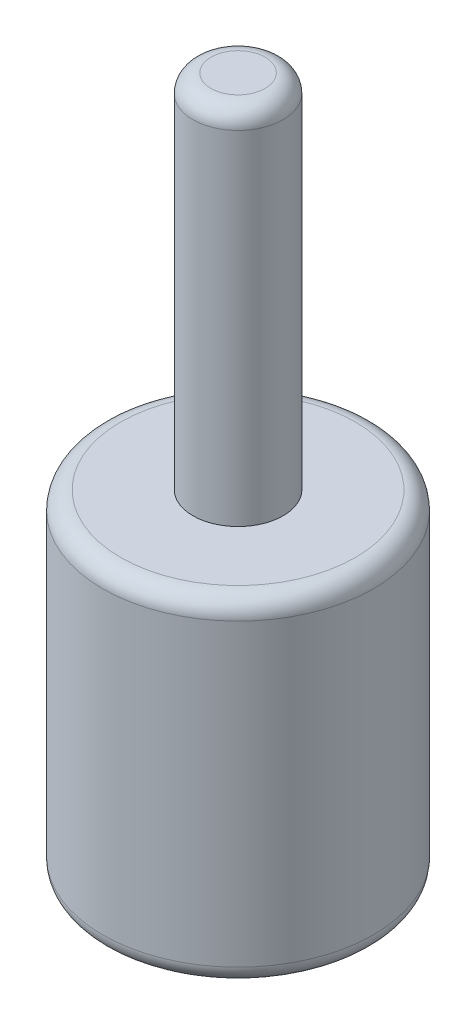
SolidWorks part; units mm, degrees
ref_plane "Plano frontal" through (0, 0, 0) normal (0, 0, 1) x (1, 0, 0)
ref_plane "Plano superior" through (0, 0, 0) normal (0, 1, 0) x (1, 0, 0)
ref_plane "Plano direito" through (0, 0, 0) normal (1, 0, 0) x (0, 0, -1)
sketch "Esboço1" plane through (0, 0, 0) normal (0, 1, 0) x (1, 0, 0)
  circle A0 centre (-2.1312, 0) radius 7.5
  dimension "D1" = 15
extrude "Ressalto-extrusão1" add sketch "Esboço1" along normal blind 18.6
sketch "Esboço2" plane through (0, 18.6, 0) normal (0, 1, 0) x (1, 0, 0)
  circle A0 centre (-2.1312, 0) radius 2.5
  dimension "D1" = 5
extrude "Ressalto-extrusão2" add sketch "Esboço2" along normal blind 20
fillet "Filete1" radius 1 3 edges at (-2.1312, 38.6, 2.5) (-2.1312, 18.6, 7.5) (-2.1312, 0, 7.5)
